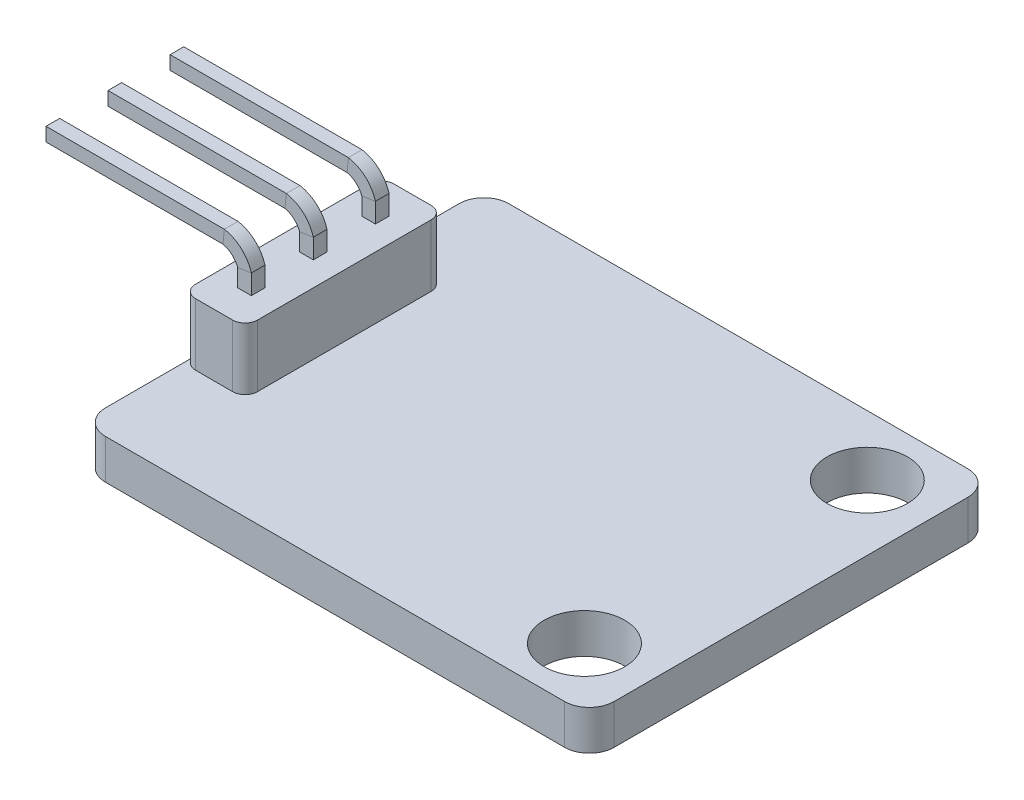
SolidWorks part; units mm, degrees
ref_plane "Front Plane" through (0, 0, 0) normal (0, 0, 1) x (1, 0, 0)
ref_plane "Top Plane" through (0, 0, 0) normal (0, 1, 0) x (1, 0, 0)
ref_plane "Right Plane" through (0, 0, 0) normal (1, 0, 0) x (0, 0, -1)
sketch "Sketch1" plane through (0, 0, 0) normal (0, 1, 0) x (1, 0, 0)
  line L0 (7.625, 7.325) -> (7.625, 8.125) construction
  line L1 (-10.25, -8.125) -> (10.25, -8.125)
  line L2 (-10.25, -8.125) -> (-10.25, 8.125)
  line L3 (-10.25, 8.125) -> (10.25, 8.125)
  line L4 (10.25, -8.125) -> (10.25, 8.125)
  line L5 (-10.25, -8.125) -> (10.25, 8.125) construction
  line L6 (-10.25, 8.125) -> (10.25, -8.125) construction
  line L7 (9.25, 5.7) -> (10.25, 5.7) construction
  line L8 (0, 0) -> (-5.4428, 0) construction
  circle A0 centre (7.625, 5.7) radius 1.625
  circle A1 centre (7.625, -5.7) radius 1.625
  point P0 (0, 0)
  dimension "D3" = 3.25
  dimension "D1" = 20.5
  dimension "D2" = 16.25
extrude "Boss-Extrude1" add sketch "Sketch1" along normal blind 1.6
fillet "Fillet1" radius 1 4 edges at (-10.25, 0.8, -8.125) (-10.25, 0.8, 8.125) (10.25, 0.8, -8.125) (10.25, 0.8, 8.125)
sketch "Sketch2" plane through (0, 1.6, 0) normal (0, 1, 0) x (1, 0, 0)
  line L0 (-10.25, 7.125) -> (-10.25, -7.125) construction
  line L1 (-10.25, -4) -> (-7.75, -4)
  line L2 (-10.25, -4) -> (-10.25, 4)
  line L3 (-10.25, 4) -> (-7.75, 4)
  line L4 (-7.75, -4) -> (-7.75, 4)
  line L5 (-10.25, -4) -> (-7.75, 4) construction
  line L6 (-10.25, 4) -> (-7.75, -4) construction
  point P0 (-9, 0)
  dimension "D1" = 8
  dimension "D2" = 2.5
extrude "Boss-Extrude2" add sketch "Sketch2" along normal blind 2.5
fillet "Fillet2" radius 0.5 4 edges at (-10.25, 2.85, -4) (-10.25, 2.85, 4) (-7.75, 2.85, -4) (-7.75, 2.85, 4)
sketch "Sketch3" plane through (0, 0, 0) normal (0, 0, 1) x (1, 0, 0)
  line L0 (-9, 4.1) -> (-9, 4.85)
  line L1 (-9.75, 4.1) -> (-8.25, 4.1) construction
  line L2 (-9.8399, 5.6) -> (-17, 5.6)
  arc A0 (-9, 4.85) -> (-9.8399, 5.6) centre (-10.0516, 4.5176) ccw
sketch "Sketch4" plane through (0, 4.1, 0) normal (0, 1, 0) x (1, 0, 0)
  line L0 (-9.8399, 0) -> (-9, 0) construction
  line L2 (-9.275, -0.275) -> (-8.725, -0.275)
  line L3 (-9.275, -0.275) -> (-9.275, 0.275)
  line L4 (-9.275, 0.275) -> (-8.725, 0.275)
  line L5 (-8.725, -0.275) -> (-8.725, 0.275)
  line L6 (-9.275, -0.275) -> (-8.725, 0.275) construction
  line L7 (-9.275, 0.275) -> (-8.725, -0.275) construction
  point P0 (-9, 0)
ref_plane "Plane1" through (0, 0, 2.5) normal (0, 0, 1) x (1, 0, 0)
ref_plane "Plane2" through (0, 0, -2.5) normal (0, 0, 1) x (1, 0, 0)
sketch "Sketch5" plane through (0, 0, -2.5) normal (0, 0, 1) x (1, 0, 0)
  line L0 (-9, 4.1) -> (-9, 4.85) construction
  line L1 (-9.8399, 5.6) -> (-17, 5.6) construction
  line L2 (-9, 4.1) -> (-9, 4.85)
  line L3 (-9.8399, 5.6) -> (-17, 5.6)
  arc A0 (-9, 4.85) -> (-9.8399, 5.6) centre (-10.0516, 4.5176) ccw construction
  arc A1 (-9, 4.85) -> (-9.8399, 5.6) centre (-10.0516, 4.5176) ccw
sketch "Sketch6" plane through (0, 0, 2.5) normal (0, 0, 1) x (1, 0, 0)
  line L0 (-9, 4.1) -> (-9, 4.85) construction
  line L1 (-9.8399, 5.6) -> (-17, 5.6) construction
  line L2 (-9, 4.1) -> (-9, 4.85)
  line L3 (-9.8399, 5.6) -> (-17, 5.6)
  arc A0 (-9, 4.85) -> (-9.8399, 5.6) centre (-10.0516, 4.5176) ccw construction
  arc A1 (-9, 4.85) -> (-9.8399, 5.6) centre (-10.0516, 4.5176) ccw
sketch "Sketch8" plane through (0, 4.1, 0) normal (0, 1, 0) x (1, 0, 0)
  line L1 (-9.2761, 2.2279) -> (-8.7261, 2.2279)
  line L2 (-9.2761, 2.2279) -> (-9.2761, 2.7779)
  line L3 (-9.2761, 2.7779) -> (-8.7261, 2.7779)
  line L4 (-8.7261, 2.2279) -> (-8.7261, 2.7779)
  line L5 (-9.2761, 2.2279) -> (-8.7261, 2.7779) construction
  line L6 (-9.2761, 2.7779) -> (-8.7261, 2.2279) construction
  point P0 (-9.0011, 2.5029)
sketch "Sketch9" plane through (0, 4.1, 0) normal (0, 1, 0) x (1, 0, 0)
  line L1 (-9.275, -2.7736) -> (-8.725, -2.7736)
  line L2 (-9.275, -2.7736) -> (-9.275, -2.2236)
  line L3 (-9.275, -2.2236) -> (-8.725, -2.2236)
  line L4 (-8.725, -2.7736) -> (-8.725, -2.2236)
  line L5 (-9.275, -2.7736) -> (-8.725, -2.2236) construction
  line L6 (-9.275, -2.2236) -> (-8.725, -2.7736) construction
  point P0 (-9, -2.4986)
sweep "Sweep2" add profiles "Sketch8" path "Sketch5"
sweep "Sweep3" add profiles "Sketch9" path "Sketch6"
sweep "Sweep4" add profiles "Sketch4" path "Sketch3"
